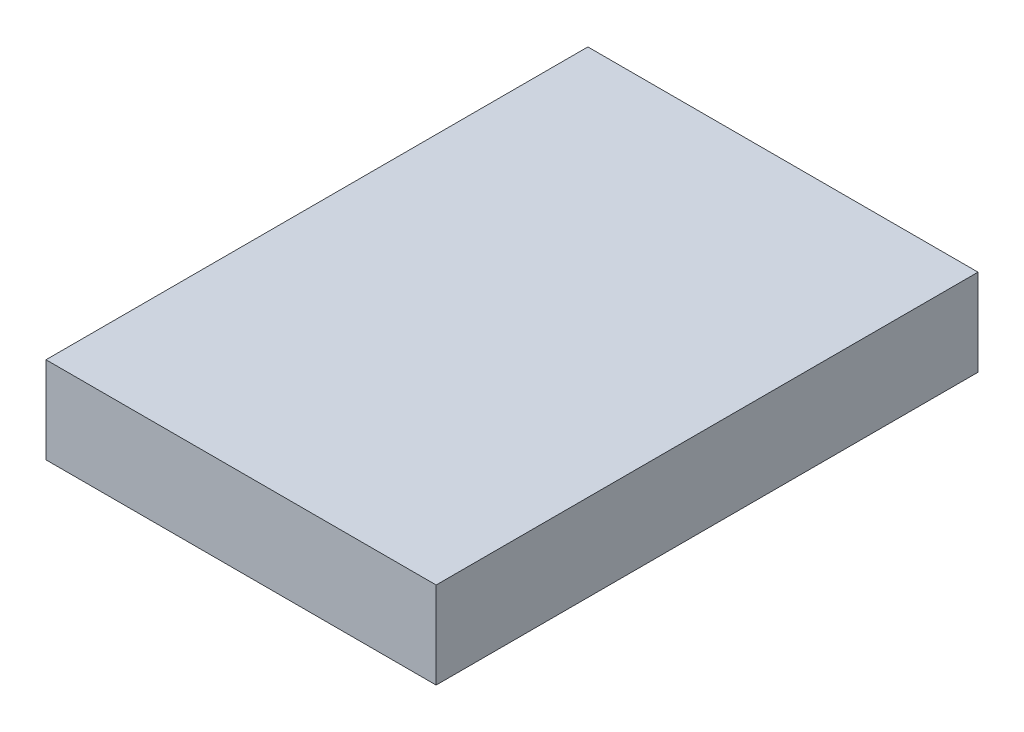
SolidWorks part; units mm, degrees
ref_plane "Front Plane" through (0, 0, 0) normal (0, 0, 1) x (1, 0, 0)
ref_plane "Top Plane" through (0, 0, 0) normal (0, 1, 0) x (1, 0, 0)
ref_plane "Right Plane" through (0, 0, 0) normal (1, 0, 0) x (0, 0, -1)
sketch "Sketch1" plane through (0, 0, 0) normal (0, 1, 0) x (1, 0, 0)
  line L0 (-4, 13) -> (4, 13)
  line L2 (-4, 5.5) -> (-4, 4.899)
  line L4 (4, 5.5) -> (4, 4.899)
  line L6 (-9, 16) -> (9, 16)
  line L7 (-4, 5.5) -> (-4, 13)
  line L8 (4, 5.5) -> (4, 13)
  line L9 (-9, 16) -> (-9, -9)
  line L10 (-9, -9) -> (9, -9)
  line L11 (9, 16) -> (9, -9)
  arc A0 (-4.2857, 4.1991) -> (4.2857, 4.1991) centre (0, 0) ccw
  arc A1 (-4.2857, 4.1991) -> (-4, 4.899) centre (-5, 4.899) ccw
  arc A2 (4.2857, 4.1991) -> (4, 4.899) centre (5, 4.899) cw
  point P19 (-7.5, 0)
  point P22 (7.5, 0)
  point P23 (0, -7.5)
  dimension "D1" = 12
  dimension "D4" = 1
  dimension "D6" = 1
  dimension "D2" = 4
  dimension "D3" = 4
  dimension "D5" = 13
  dimension "D8" = 9
  dimension "D7" = 3
  dimension "D9" = 9
  dimension "D10" = 9
extrude "Boss-Extrude1" add sketch "Sketch1" along normal blind 1
sketch "Sketch2" plane through (0, 1, 0) normal (0, 1, 0) x (1, 0, 0)
  line L1 (-9, 16) -> (9, 16)
  line L2 (-9, 16) -> (-9, -9)
  line L3 (-9, -9) -> (9, -9)
  line L4 (9, 16) -> (9, -9)
extrude "Boss-Extrude2" add sketch "Sketch2" along normal blind 3
